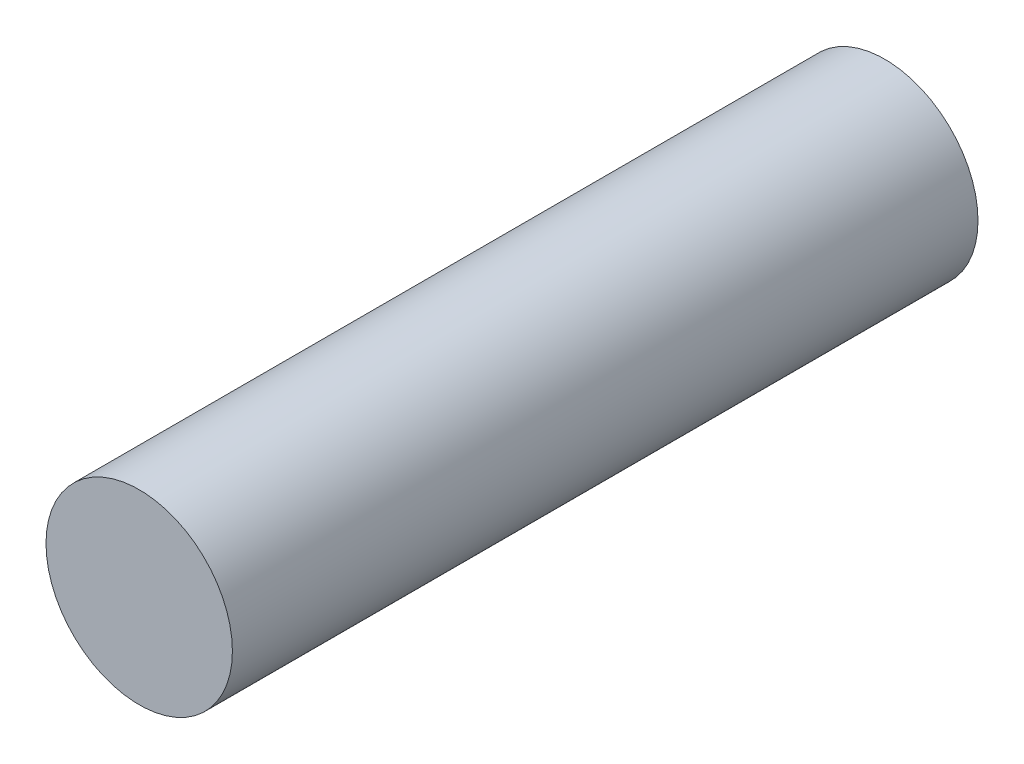
SolidWorks part; units mm, degrees
ref_plane "Front Plane" through (0, 0, 0) normal (1, 0, 0) x (0, 1, 0)
ref_plane "Top Plane" through (0, 0, 0) normal (0, 0, 1) x (0, 1, 0)
ref_plane "Right Plane" through (0, 0, 0) normal (0, 1, 0) x (-1, 0, 0)
sketch "Sketch1" plane through (0, 0, 0) normal (0, 0, 1) x (0, 1, 0)
  circle A0 centre (0, 0) radius 3.175
  dimension "D1" = 6.35
extrude "Boss-Extrude1" add sketch "Sketch1" along normal blind 25.4 contours A0
